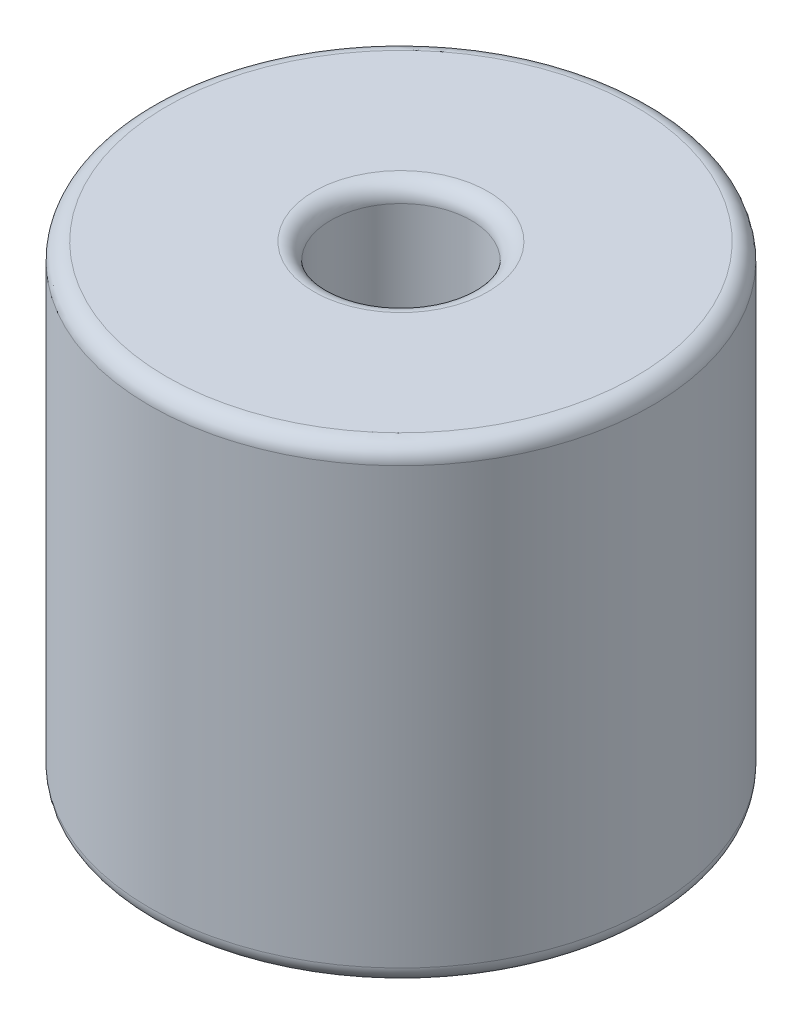
SolidWorks part; units mm, degrees
ref_plane "Front Plane" through (0, 0, 0) normal (0, 0, 1) x (1, 0, 0)
ref_plane "Top Plane" through (0, 0, 0) normal (0, 1, 0) x (1, 0, 0)
ref_plane "Right Plane" through (0, 0, 0) normal (1, 0, 0) x (0, 0, -1)
sketch "Sketch1" plane through (0, 0, 0) normal (0, 1, 0) x (1, 0, 0)
  circle A0 centre (0, 0) radius 2.1
  circle A1 centre (0, 0) radius 7.5
  dimension "D1" = 4.2
  dimension "D2" = 15
extrude "Boss-Extrude1" add sketch "Sketch1" along normal blind 14
fillet "Fillet1" radius 0.5 4 edges at (0, 0, 2.1) (0, 14, 2.1) (0, 0, 7.5) (0, 14, 7.5)
